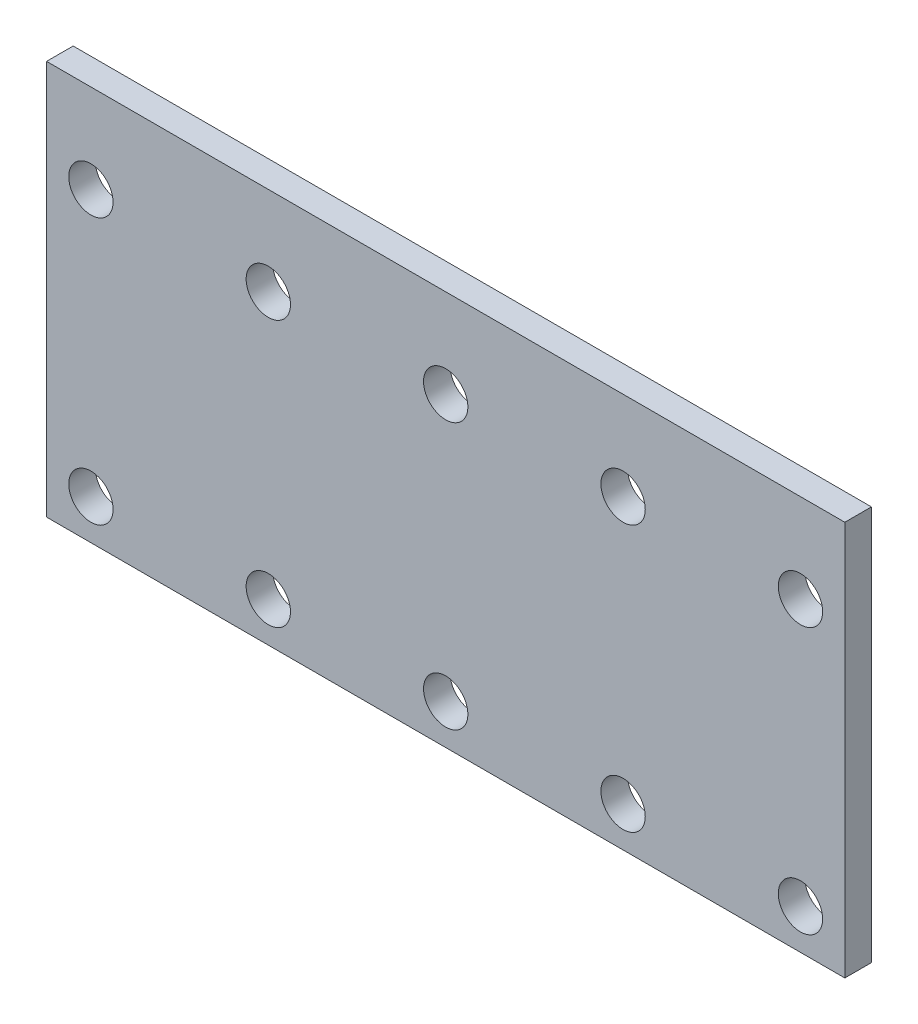
SolidWorks part; units mm, degrees
material "ABS"
ref_plane "Front Plane" through (0, 0, 0) normal (0, 0, 1) x (1, 0, 0)
ref_plane "Top Plane" through (0, 0, 0) normal (0, 1, 0) x (1, 0, 0)
ref_plane "Right Plane" through (0, 0, 0) normal (1, 0, 0) x (0, 0, -1)
sketch "Sketch1" plane through (0, 0, 0) normal (0, 0, 1) x (1, 0, 0)
  line L0 (0, 14.5) -> (0, 44.5)
  line L1 (0, 0) -> (90, 0)
  line L2 (0, 0) -> (0, 14.5)
  line L3 (0, 14.5) -> (90, 14.5)
  line L4 (90, 0) -> (90, 14.5)
  line L5 (0, 44.5) -> (90, 44.5)
  line L6 (90, 44.5) -> (90, 14.5)
  line L7 (0, 4.5) -> (90, 4.5) construction
  line L8 (0, 34.5) -> (90, 34.5) construction
  line L9 (5, 34.5) -> (5, 4.5) construction
  circle A0 centre (5, 34.5) radius 2.5
  circle A1 centre (5, 4.5) radius 2.5
  circle A2 centre (25, 4.5) radius 2.5
  circle A3 centre (25, 34.5) radius 2.5
  circle A4 centre (45, 4.5) radius 2.5
  circle A5 centre (45, 34.5) radius 2.5
  circle A6 centre (65, 4.5) radius 2.5
  circle A7 centre (65, 34.5) radius 2.5
  circle A8 centre (85, 4.5) radius 2.5
  circle A9 centre (85, 34.5) radius 2.5
  point P4 (5, 37)
  point P16 (5, 2)
  dimension "D4" = 5
  dimension "D5" = 5
  dimension "D1" = 10
  dimension "D2" = 20
  dimension "D3" = 90
  dimension "D6" = 5
  dimension "D8" = 2
  dimension "D9" = 10
  dimension "D7" = 5
extrude "Boss-Extrude1" add sketch "Sketch1" along normal blind 3
sketch "Sketch2" [suppressed] plane through (0, 0, 0) normal (0, 0, 1) x (1, 0, 0)
  line L0 (0, 20) -> (20, 20) construction
  line L1 (0, 0) -> (40, 0)
  line L2 (0, 0) -> (0, 30)
  line L3 (0, 30) -> (40, 30)
  line L4 (40, 0) -> (40, 30)
  line L5 (20, 20) -> (40, 20) construction
  circle A0 centre (10, 20) radius 2.5
  circle A1 centre (30, 20) radius 2.5
  circle A2 centre (20, 20) radius 2.5
  point P7 (10, 20)
  point P9 (30, 20)
  dimension "D1" = 5
  dimension "D2" = 30
  dimension "D3" = 20
  dimension "D4" = 40
extrude "Boss-Extrude2" [suppressed] add sketch "Sketch2" along normal blind 3
sketch "Sketch3" [suppressed] plane through (0, 0, 0) normal (0, 1, 0) x (1, 0, 0)
  line L0 (0, -10) -> (20, -10) construction
  line L1 (0, 0) -> (40, 0)
  line L2 (0, 0) -> (0, -15)
  line L3 (0, -15) -> (40, -15)
  line L4 (40, 0) -> (40, -15)
  line L5 (20, -10) -> (40, -10) construction
  circle A0 centre (10, -10) radius 2.5
  circle A1 centre (30, -10) radius 2.5
  point P14 (10, -12.5)
  dimension "D3" = 5
  dimension "D1" = 2.5
  dimension "D2" = 10
extrude "Boss-Extrude3" [suppressed] add sketch "Sketch3" along normal blind 3
sketch "Sketch6" [suppressed] plane through (0, 0, 3) normal (0, 0, 1) x (1, 0, 0)
  line L0 (7.5, 20) -> (5.75, 20) construction
  line L1 (5.75, 15.75) -> (5.75, 24.25)
  line L2 (5.75, 24.25) -> (14.25, 24.25)
  line L3 (10, 24.25) -> (10, 22.5) construction
  line L4 (14.25, 15.75) -> (14.25, 24.25)
  line L5 (5.75, 15.75) -> (14.25, 15.75)
  line L6 (20, 30) -> (20, 3) construction
  line L7 (40, 30) -> (0, 30) construction
  line L8 (0, 3) -> (40, 3) construction
  line L9 (34.25, 15.75) -> (25.75, 15.75)
  line L10 (34.25, 15.75) -> (34.25, 24.25)
  line L11 (34.25, 24.25) -> (25.75, 24.25)
  line L12 (25.75, 15.75) -> (25.75, 24.25)
  line L13 (17.5, 20) -> (15.75, 20) construction
  line L14 (15.75, 15.75) -> (15.75, 24.25)
  line L15 (15.75, 24.25) -> (24.25, 24.25)
  line L16 (20, 24.25) -> (20, 22.5) construction
  line L17 (24.25, 15.75) -> (24.25, 24.25)
  line L18 (15.75, 15.75) -> (24.25, 15.75)
  circle A0 centre (10, 20) radius 2.5 construction
  circle A1 centre (20, 20) radius 2.5 construction
  point P11 (14.25, 20)
  point P34 (24.25, 20)
  dimension "D1" = 2
sketch "Sketch4" [suppressed] plane through (0, 3, 0) normal (0, 1, 0) x (1, 0, 0)
  line L1 (5.7783, -15) -> (5.7783, -5.75)
  line L2 (0, -15) -> (40, -15) construction
  line L3 (5.7783, -5.75) -> (14.2217, -5.75)
  line L4 (10, -5.75) -> (10, -7.5) construction
  line L5 (7.5283, -10.375) -> (5.7783, -10.375) construction
  line L6 (14.2217, -15) -> (14.2217, -5.75)
  line L7 (5.7783, -15) -> (14.2217, -15)
  line L8 (20, -15) -> (20, -3) construction
  line L9 (0, -3) -> (40, -3) construction
  line L10 (32.4717, -10.375) -> (34.2217, -10.375) construction
  line L11 (30, -5.75) -> (30, -7.5) construction
  line L12 (34.2217, -15) -> (25.7783, -15)
  line L13 (25.7783, -15) -> (25.7783, -5.75)
  line L14 (34.2217, -5.75) -> (25.7783, -5.75)
  line L15 (34.2217, -15) -> (34.2217, -5.75)
  circle A2 centre (10, -10) radius 2.5 construction
  dimension "D1" = 2
fillet "Fillet2" [suppressed] radius 35
extrude "Cut-Extrude2" [suppressed] cut sketch "Sketch4" along normal through all
extrude "Cut-Extrude4" [suppressed] cut sketch "Sketch6" along normal through all
fillet "Fillet4" [suppressed] radius 1
